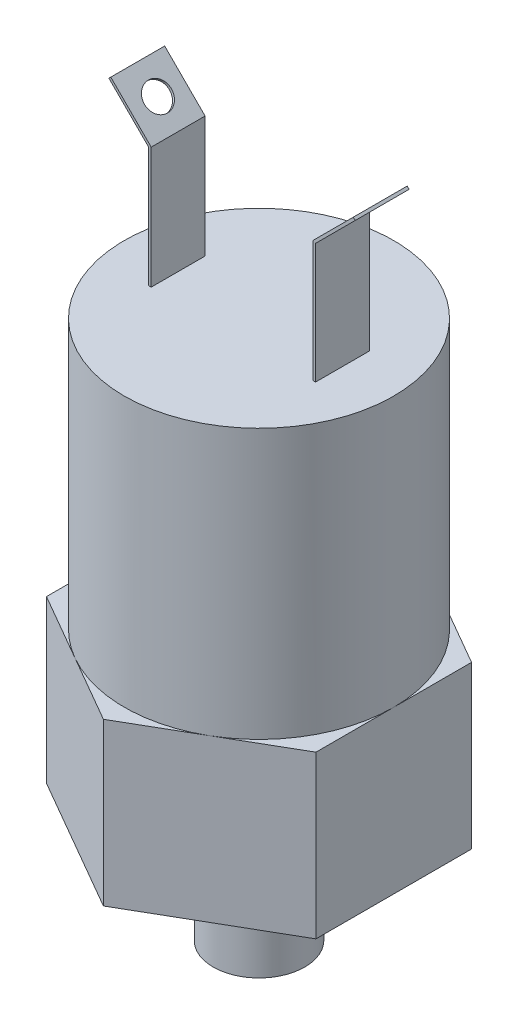
SolidWorks part; units mm, degrees
ref_plane "Front Plane" through (0, 0, 0) normal (0, 0, 1) x (1, 0, 0)
ref_plane "Top Plane" through (0, 0, 0) normal (0, 1, 0) x (1, 0, 0)
ref_plane "Right Plane" through (0, 0, 0) normal (1, 0, 0) x (0, 0, -1)
sketch "Sketch1" plane through (0, 0, 0) normal (0, 1, 0) x (1, 0, 0)
  circle A0 centre (0, 0) radius 4.318
  dimension "D1" = 8.636
extrude "Boss-Extrude1" add sketch "Sketch1" along normal blind 10.16
cosmetic thread "Cosmetic Thread1" parameters "D2"=7.636
sketch "Sketch2" plane through (0, 10.16, 0) normal (0, 1, 0) x (1, 0, 0)
  line L1 (0, 14.6647) -> (-12.7, 7.3323)
  line L2 (-12.7, 7.3323) -> (-12.7, -7.3323)
  line L3 (-12.7, -7.3323) -> (0, -14.6647)
  line L4 (0, -14.6647) -> (12.7, -7.3323)
  line L5 (12.7, -7.3323) -> (12.7, 7.3323)
  line L6 (12.7, 7.3323) -> (0, 14.6647)
  circle A0 centre (0, 0) radius 12.7 construction
  dimension "D1" = 25.4
extrude "Boss-Extrude2" add sketch "Sketch2" along normal blind 15.24
sketch "Sketch3" plane through (0, 25.4, 0) normal (0, 1, 0) x (1, 0, 0)
  circle A0 centre (0, 0) radius 12.7
  dimension "D1" = 25.4
extrude "Boss-Extrude3" add sketch "Sketch3" along normal blind 25.4
sketch "Sketch4" plane through (0, 0, 0) normal (0, 0, 1) x (1, 0, 0)
  line L0 (7.62, 50.8) -> (7.62, 62.23)
  line L1 (12.7, 50.8) -> (-12.7, 50.8) construction
  line L2 (7.62, 62.23) -> (11.43, 66.04)
  line L3 (12.7, 25.4) -> (12.7, 50.8) construction
  dimension "D1" = 15.24
  dimension "D2" = 45
  dimension "D3" = 11.43
  dimension "D4" = 5.08
extrude "Extrude-Thin1" add sketch "Sketch4" along normal mid plane 5.08 thin
sketch "Sketch5" plane through (-27.305, 27.305, 0) normal (-0.7071, 0.7071, 0) x (0, 0, 1)
  line L0 (-2.54, 54.7796) -> (2.54, 49.3914) construction
  line L1 (2.54, 54.7796) -> (-2.54, 49.3914) construction
  circle A0 centre (0, 52.0855) radius 1.27
  dimension "D1" = 2.54
extrude "Cut-Extrude1" cut sketch "Sketch5" against normal up to next
mirror "Mirror1" about plane through (0, 0, 0) normal (1, 0, 0) of "Cut-Extrude1", "Extrude-Thin1"
